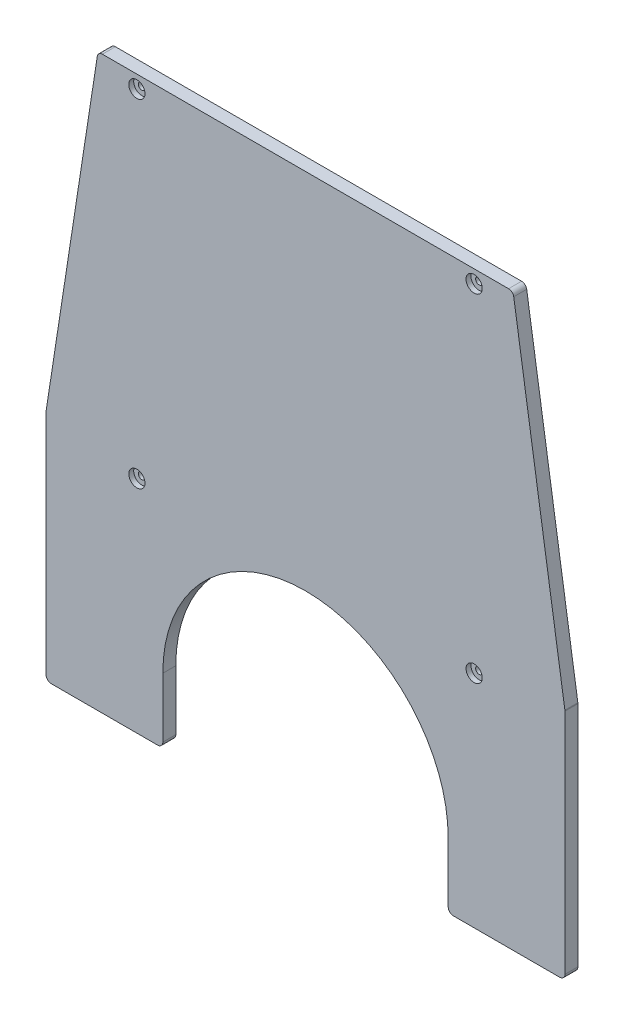
SolidWorks part; units mm, degrees
ref_plane "Front Plane" through (0, 0, 0) normal (0, 0, 1) x (1, 0, 0)
ref_plane "Top Plane" through (0, 0, 0) normal (0, 1, 0) x (1, 0, 0)
ref_plane "Right Plane" through (0, 0, 0) normal (1, 0, 0) x (0, 0, -1)
sketch "Sketch1" plane through (0, 0, 0) normal (0, 0, 1) x (1, 0, 0)
  line L0 (139.7, 0) -> (254, 0)
  line L1 (139.7, 0) -> (-139.7, 0)
  line L3 (203.2, 495.3) -> (-203.2, 495.3)
  line L5 (254, 0) -> (254, 165.1)
  line L6 (254, 165.1) -> (203.2, 495.3)
  line L7 (139.7, 0) -> (139.7, -63.5)
  line L8 (0, 0) -> (254, 0)
  line L10 (139.7, -63.5) -> (254, -63.5)
  line L11 (254, 0) -> (254, -63.5)
  line L12 (0, 495.3) -> (0, 139.7)
  line L13 (-139.7, 0) -> (-254, 0)
  line L14 (-254, 0) -> (-254, 165.1)
  line L15 (-139.7, -63.5) -> (-254, -63.5)
  line L16 (-139.7, 0) -> (-139.7, -63.5)
  line L17 (-254, 0) -> (-254, -63.5)
  line L18 (-254, 165.1) -> (-203.2, 495.3)
  circle A0 centre (0, 0) radius 139.7
  circle A2 centre (0, 0) radius 254 construction
  dimension "D1" = 279.4
  dimension "D2" = 203.2
  dimension "D3" = 355.6
  dimension "D4" = 114.3
  dimension "D5" = 165.1
  dimension "D6" = 334.0848
  dimension "D7" = 63.5
  dimension "D8" = 63.5
  dimension "D9" = 355.6
extrude "Boss-Extrude3" add sketch "Sketch1" along normal blind 12.7 contours A0 L12 L3 L18 L14 L13 | L13 L17 L15 L16 | A0 L0 L5 L6 L3 L12 | L11 L0 L7 L10
fillet "Fillet1" radius 5.08 8 edges at (-254, 165.1, 6.35) (-203.2, 495.3, 6.35) (203.2, 495.3, 6.35) (254, 165.1, 6.35) (254, -63.5, 6.35) (139.7, -63.5, 6.35) (-139.7, -63.5, 6.35) (-254, -63.5, 6.35)
hole_wizard "CBORE for 1/4 Hex Machine Screw1" positions "Sketch6" profile "Sketch7" counterbore size "1/4" standard "ANSI Inch" end condition through all
sketch "Sketch6" plane through (0, 0, 12.7) normal (0, 0, 1) x (1, 0, 0)
  line L0 (198.8418, 495.3) -> (-198.8418, 495.3) construction
  line L1 (254, -58.42) -> (254, 164.7115) construction
  line L3 (-254, -58.42) -> (-254, 164.7115) construction
  point P0 (165.1, 482.6)
  point P2 (165.1, 152.4)
  point P4 (-165.1, 152.4)
  point P6 (-165.1, 482.6)
  dimension "D1" = 12.7
  dimension "D2" = 12.7
  dimension "D3" = 330.2
  dimension "D4" = 330.2
  dimension "D5" = 330.2
  dimension "D6" = 88.9
  dimension "D7" = 88.9
sketch "Sketch7" plane through (165.1, 482.6, 12.7) normal (1, 0, 0) x (0, -1, 0)
  line L0 (0, 0) -> (0, 12.7)
  line L1 (0, 12.7) -> (3.3782, 12.7)
  line L3 (3.3782, 12.7) -> (3.3782, 4.826)
  line L4 (3.3782, 4.826) -> (7.9375, 4.826)
  line L5 (7.9375, 4.826) -> (7.9375, 0)
  line L7 (7.9375, 0) -> (0, 0)
  line L11 (0, -6.35) -> (0, 107.95) construction
  dimension "Thru Hole Dia." = 6.7564
  dimension "Thru Hole Depth" = 12.7
  dimension "C'Bore Dia." = 15.875
  dimension "C'Bore Depth" = 4.826
